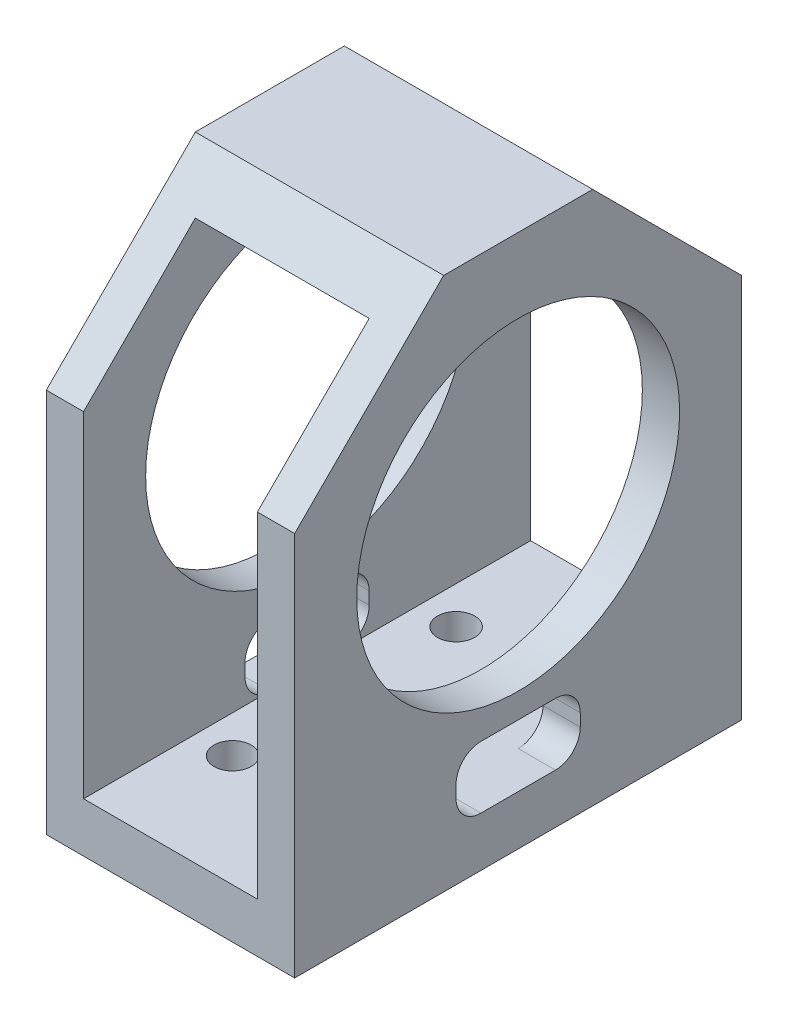
SolidWorks part; units mm, degrees
material "6061 合金"
ref_plane "前视基准面" through (0, 0, 0) normal (0, 0, 1) x (1, 0, 0)
ref_plane "上视基准面" through (0, 0, 0) normal (0, 1, 0) x (1, 0, 0)
ref_plane "右视基准面" through (0, 0, 0) normal (1, 0, 0) x (0, 0, -1)
sketch "草图1" plane through (0, 0, 0) normal (0, 1, 0) x (1, 0, 0)
  line L1 (-10, -18) -> (10, -18)
  line L2 (-10, -18) -> (-10, 18)
  line L3 (-10, 18) -> (10, 18)
  line L4 (10, -18) -> (10, 18)
  line L5 (-10, -18) -> (10, 18) construction
  line L6 (-10, 18) -> (10, -18) construction
  point P0 (0, 0)
  dimension "D1" = 20
  dimension "D2" = 36
extrude "凸台-拉伸1" add sketch "草图1" along normal blind 4
sketch "草图2" plane through (0, 4, 0) normal (0, 1, 0) x (1, 0, 0)
  line L0 (-10, -18) -> (10, -18) construction
  line L1 (-10, 18) -> (-7, 18)
  line L2 (-10, 18) -> (-10, -18)
  line L3 (-10, -18) -> (-7, -18)
  line L4 (-7, 18) -> (-7, -18)
  line L5 (0, 18) -> (0, -18) construction
  line L6 (10, 18) -> (-10, 18) construction
  line L7 (10, -18) -> (7, -18)
  line L8 (7, 18) -> (7, -18)
  line L9 (10, 18) -> (7, 18)
  line L10 (10, 18) -> (10, -18)
  dimension "D1" = 3
extrude "凸台-拉伸2" add sketch "草图2" along normal blind 36
sketch "草图3" plane through (0, 40, 0) normal (0, 1, 0) x (1, 0, 0)
  line L1 (-10, 18) -> (10, 18)
  line L2 (-10, 18) -> (-10, -18)
  line L3 (-10, -18) -> (10, -18)
  line L4 (10, 18) -> (10, -18)
extrude "凸台-拉伸3" add sketch "草图3" along normal blind 3
sketch "草图4" plane through (10, 0, 0) normal (1, 0, 0) x (0, 0, -1)
  line L0 (0, 0) -> (0, 43) construction
  line L1 (-18, 43) -> (18, 43) construction
  line L2 (-18, 0) -> (18, 0) construction
  circle A0 centre (0, 24) radius 13
  dimension "D2" = 26
  dimension "D1" = 24
extrude "切除-拉伸1" cut sketch "草图4" against normal through all
sketch "草图5" plane through (10, 0, 0) normal (1, 0, 0) x (0, 0, -1)
  line L0 (0, 43) -> (0, 0) construction
  line L1 (-18, 43) -> (18, 43) construction
  line L2 (-6, 43) -> (-18, 31)
  line L3 (-18, 43) -> (-18, 0) construction
  line L4 (-18, 31) -> (-18, 43)
  line L5 (-18, 43) -> (-6, 43)
  line L6 (18, 31) -> (18, 43)
  line L7 (6, 43) -> (18, 31)
  line L8 (18, 43) -> (6, 43)
  dimension "D1" = 12
  dimension "D2" = 12
extrude "切除-拉伸2" cut sketch "草图5" against normal through all
sketch "草图6" plane through (0, 4, 0) normal (0, 1, 0) x (1, 0, 0)
  line L0 (-10, 0) -> (10, 0) construction
  line L1 (-4, -9) -> (4, -9) construction
  line L2 (-4, -9) -> (-4, 9) construction
  line L3 (-4, 9) -> (4, 9) construction
  line L4 (4, -9) -> (4, 9) construction
  line L5 (-4, -9) -> (4, 9) construction
  line L6 (-4, 9) -> (4, -9) construction
  line L7 (-10, 6) -> (-10, -6) construction
  line L8 (10, -6) -> (10, 6) construction
  line L9 (0, 18) -> (0, -18) construction
  line L10 (7, 18) -> (-7, 18) construction
  line L11 (-7, -18) -> (7, -18) construction
  circle A0 centre (4, 9) radius 1.5
  circle A1 centre (-4, 9) radius 1.5
  circle A2 centre (4, -9) radius 1.5
  circle A3 centre (-4, -9) radius 1.5
  point P0 (0, 0)
  dimension "D3" = 3
  dimension "D1" = 18
  dimension "D2" = 8
extrude "切除-拉伸3" cut sketch "草图6" against normal blind 4
sketch "草图7" plane through (10, 0, 0) normal (1, 0, 0) x (0, 0, -1)
  line L0 (18, 4) -> (-18, 4) construction
  line L1 (-5, 4) -> (5, 4)
  line L2 (-5, 4) -> (-5, 9)
  line L3 (-5, 9) -> (5, 9)
  line L4 (5, 4) -> (5, 9)
  dimension "D1" = 10
  dimension "D2" = 5
  dimension "D3" = 5
extrude "切除-拉伸4" cut sketch "草图7" against normal through all
fillet "圆角1" radius 2 8 edges at (-8.5, 4, 5) (-8.5, 9, 5) (-8.5, 9, -5) (-8.5, 4, -5) (8.5, 4, -5) (8.5, 9, -5) (8.5, 9, 5) (8.5, 4, 5)
